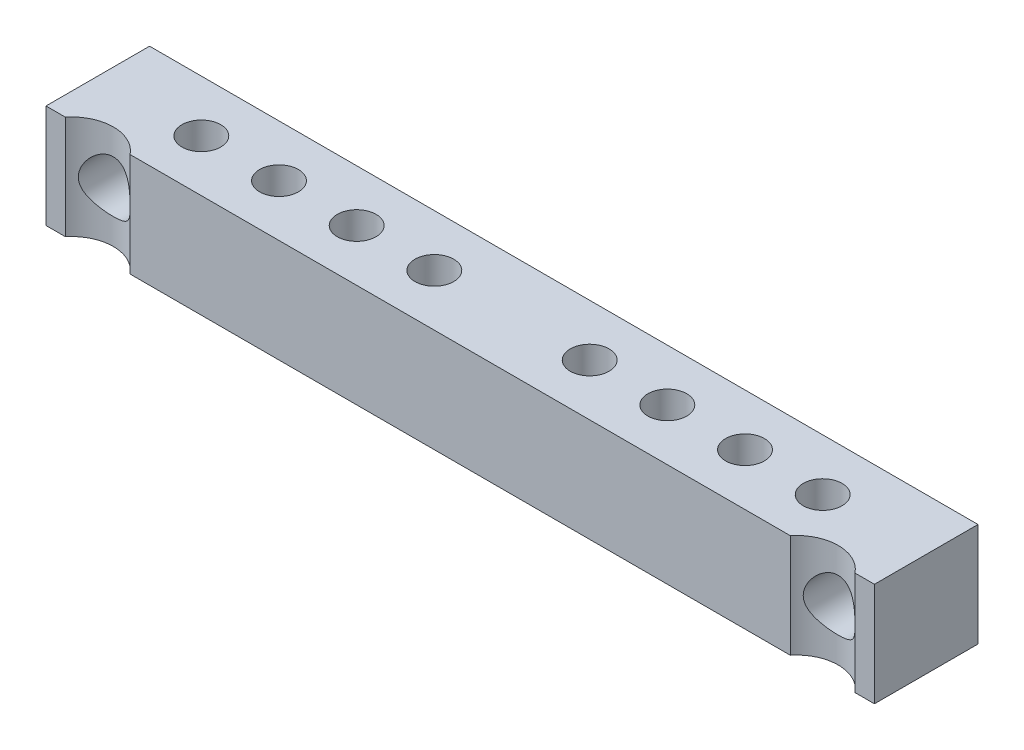
SolidWorks part; units mm, degrees
material "Aleación 1060"
ref_plane "Alzado" through (0, 0, 0) normal (0, 0, 1) x (1, 0, 0)
ref_plane "Planta" through (0, 0, 0) normal (0, 1, 0) x (1, 0, 0)
ref_plane "Vista lateral" through (0, 0, 0) normal (1, 0, 0) x (0, 0, -1)
sketch "Croquis1" plane through (0, 0, 0) normal (0, 0, 1) x (1, 0, 0)
  line L0 (16, 4) -> (16, 0) construction
  line L1 (0, 0) -> (32, 0)
  line L2 (0, 0) -> (0, 4)
  line L3 (0, 4) -> (32, 4)
  line L4 (32, 0) -> (32, 4)
  circle A0 centre (2, 2) radius 1
  circle A1 centre (30, 2) radius 1
  dimension "D3" = 2
  dimension "D5" = 2
  dimension "D1" = 32
  dimension "D2" = 4
  dimension "D4" = 2
extrude "Saliente-Extruir1" add sketch "Croquis1" along normal blind 4
sketch "Croquis2" plane through (0, 0, 0) normal (0, -1, 0) x (1, 0, 0)
  line L0 (0, 4) -> (32, 4) construction
  line L1 (16, 4) -> (16, 0) construction
  line L2 (0, 0) -> (32, 0) construction
  circle A0 centre (2, 5) radius 1.6
  circle A1 centre (13, 2) radius 0.75
  circle A2 centre (10, 2) radius 0.75
  circle A3 centre (7, 2) radius 0.75
  circle A4 centre (25, 2) radius 0.75
  circle A5 centre (22, 2) radius 0.75
  circle A6 centre (19, 2) radius 0.75
  circle A7 centre (30, 5) radius 1.6
  circle A8 centre (28, 2) radius 0.75
  circle A9 centre (4, 2) radius 0.75
  dimension "D1" = 1
  dimension "D2" = 2
  dimension "D3" = 3
  dimension "D4" = 1.5
  dimension "D5" = 3
  dimension "D6" = 2
  dimension "D7" = 2
extrude "Cortar-Extruir1" cut sketch "Croquis2" against normal up to vertex (4 mm away)
